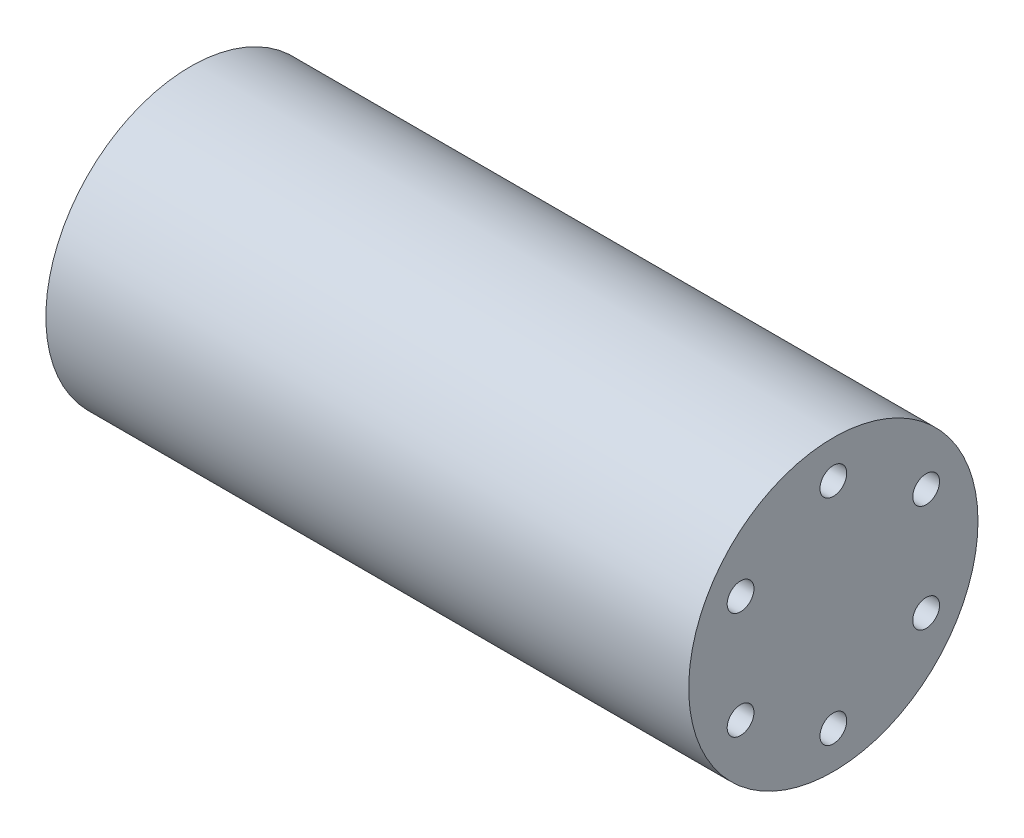
SolidWorks part; units mm, degrees
ref_plane "Front Plane" through (0, 0, 0) normal (0, 0, 1) x (1, 0, 0)
ref_plane "Top Plane" through (0, 0, 0) normal (0, 1, 0) x (1, 0, 0)
ref_plane "Right Plane" through (0, 0, 0) normal (1, 0, 0) x (0, 0, -1)
sketch "Sketch1" plane through (0, 0, 0) normal (1, 0, 0) x (0, 0, -1)
  circle A0 centre (0, 0) radius 13.5
  dimension "D1" = 27
extrude "Boss-Extrude1" add sketch "Sketch1" along normal mid plane 60
sketch "Sketch2" plane through (-30, 0, 0) normal (-1, 0, 0) x (0, 0, 1)
  circle A0 centre (0, 10) radius 1.25
  circle A1 centre (0, 0) radius 13.5 construction
  circle A2 centre (8.6603, 5) radius 1.25
  circle A3 centre (8.6603, -5) radius 1.25
  circle A4 centre (0, -10) radius 1.25
  circle A5 centre (-8.6603, -5) radius 1.25
  circle A6 centre (-8.6603, 5) radius 1.25
  point P17 (0, 0)
  dimension "D1" = 2.5
  dimension "D2" = 10
  dimension "D3" = 6
extrude "Cut-Extrude1" cut sketch "Sketch2" against normal blind 4
mirror "Mirror1" about plane through (0, 0, 0) normal (1, 0, 0) of "Cut-Extrude1"
